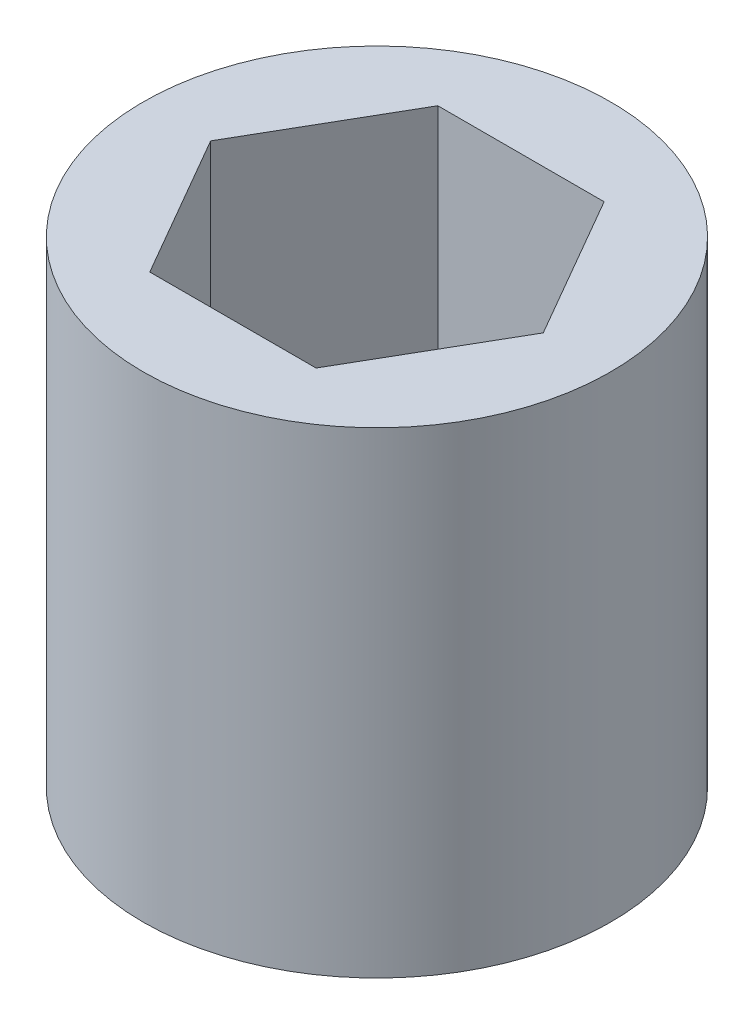
SolidWorks part; units mm, degrees
ref_plane "Front Plane" through (0, 0, 0) normal (0, 0, 1) x (1, 0, 0)
ref_plane "Top Plane" through (0, 0, 0) normal (0, 1, 0) x (1, 0, 0)
ref_plane "Right Plane" through (0, 0, 0) normal (1, 0, 0) x (0, 0, -1)
sketch "Sketch1" plane through (0, 0, 0) normal (0, 1, 0) x (1, 0, 0)
  line L1 (5.6459, 0) -> (2.823, 4.8895)
  line L2 (2.823, 4.8895) -> (-2.823, 4.8895)
  line L3 (-2.823, 4.8895) -> (-5.6459, 0)
  line L4 (-5.6459, 0) -> (-2.823, -4.8895)
  line L5 (-2.823, -4.8895) -> (2.823, -4.8895)
  line L6 (2.823, -4.8895) -> (5.6459, 0)
  circle A0 centre (0, 0) radius 4.8895 construction
  circle A1 centre (0, 0) radius 7.9375
  dimension "D1" = 9.779
  dimension "D2" = 15.875
extrude "Boss-Extrude1" add sketch "Sketch1" along normal blind 16.1798
